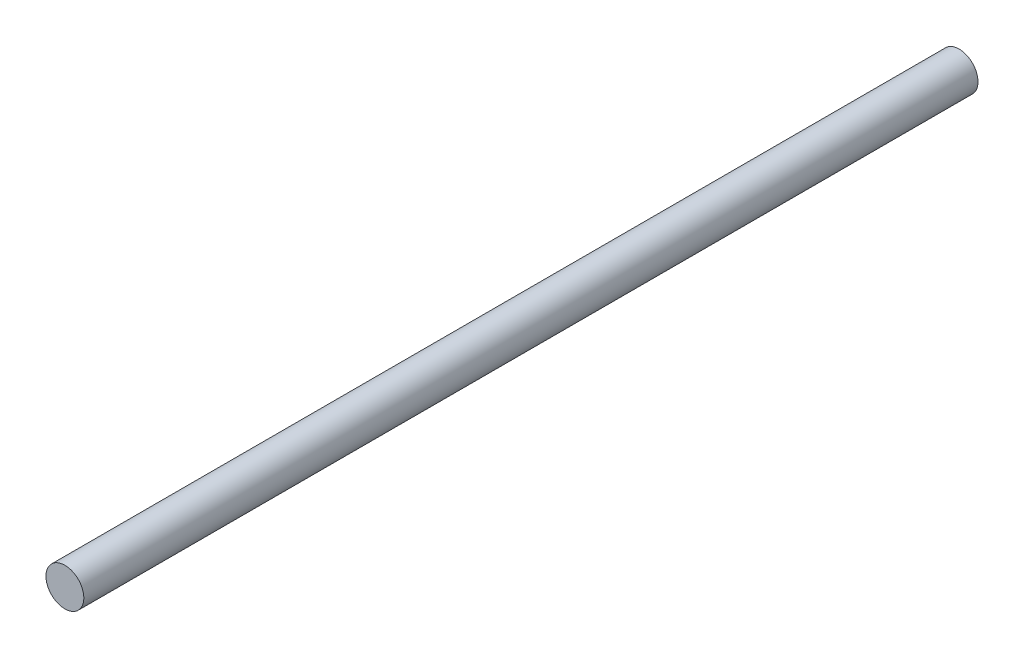
SolidWorks part; units mm, degrees
ref_plane "Front" through (0, 0, 0) normal (0, 0, 1) x (1, 0, 0)
ref_plane "Top" through (0, 0, 0) normal (0, 1, 0) x (1, 0, 0)
ref_plane "Right" through (0, 0, 0) normal (1, 0, 0) x (0, 0, -1)
sketch "Sketch1" plane through (0, 0, 0) normal (0, 0, 1) x (1, 0, 0)
  circle A0 centre (0, 13.7398) radius 3.175
  dimension "D1" = 6.35
extrude "Boss-Extrude1" add sketch "Sketch1" along normal blind 150
